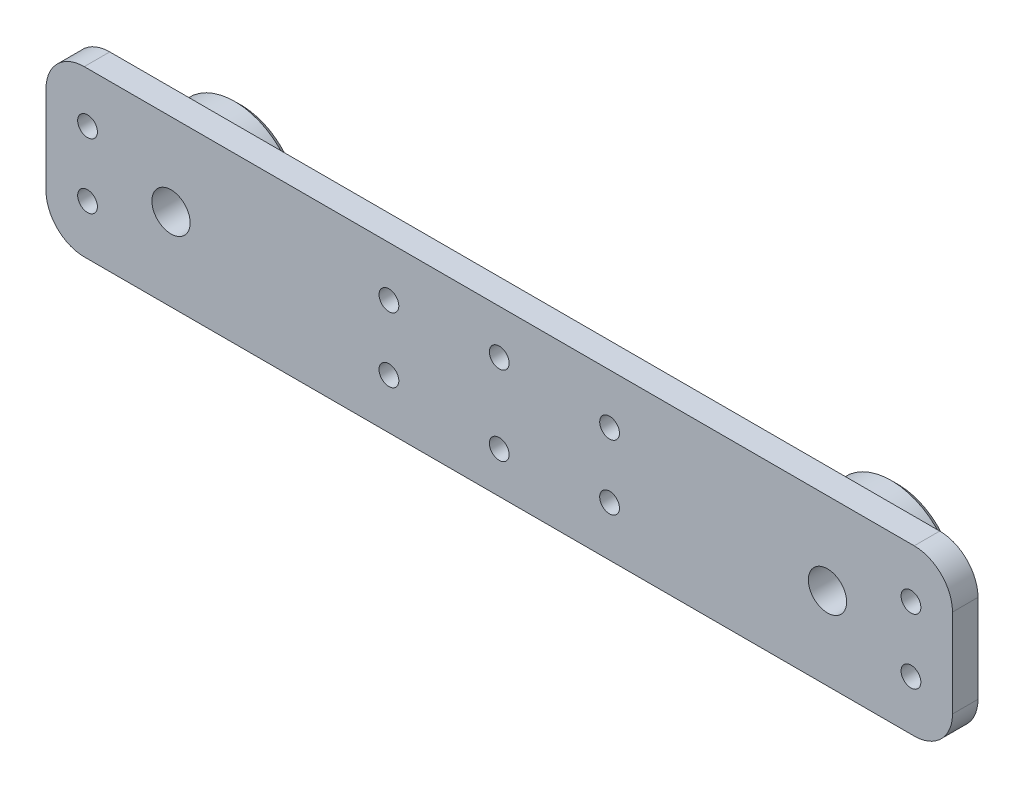
SolidWorks part; units mm, degrees
material "PET"
ref_plane "Front Plane" through (0, 0, 0) normal (0, 0, 1) x (1, 0, 0)
ref_plane "Top Plane" through (0, 0, 0) normal (0, 1, 0) x (1, 0, 0)
ref_plane "Right Plane" through (0, 0, 0) normal (1, 0, 0) x (0, 0, -1)
ref_plane "Plane1" through (0, 0, -8.279) normal (0, 0, -1) x (-1, 0, 0)
sketch "Sketch1" plane through (0, 0, -8.279) normal (0, 0, -1) x (-1, 0, 0)
  line L0 (-112, 9.158) -> (30.1427, 9.158)
  line L1 (30.1427, 9.158) -> (30.1427, 35)
  line L2 (30.1427, 35) -> (-112, 35)
  line L3 (-112, 35) -> (-112, 9.158)
extrude "Boss-Extrude1" add sketch "Sketch1" against normal blind 4
ref_plane "Plane2" through (0, 22.079, 0) normal (0, 1, 0) x (1, 0, 0)
sketch "Sketch2" plane through (0, 22.079, 0) normal (0, 1, 0) x (1, 0, 0)
  line L0 (-0.54, 15.279) -> (-10.54, 15.279)
  line L1 (-10.54, 15.279) -> (-10.54, 8.279)
  line L2 (-10.54, 8.279) -> (-0.54, 8.279)
  line L3 (-0.54, 8.279) -> (-0.54, 15.279)
  line L4 (-10.54, 15.279) -> (-10.54, 8.279) construction
revolve "Revolve1" add sketch "Sketch2" angle 360 about L4
sketch "Sketch3" plane through (0, 22.079, 0) normal (0, 1, 0) x (1, 0, 0)
  line L0 (102.397, 15.279) -> (92.397, 15.279)
  line L1 (92.397, 15.279) -> (92.397, 8.279)
  line L2 (92.397, 8.279) -> (102.397, 8.279)
  line L3 (102.397, 8.279) -> (102.397, 15.279)
  line L4 (92.397, 15.279) -> (92.397, 8.279) construction
revolve "Revolve2" add sketch "Sketch3" angle 360 about L4
hole_wizard "Ø3.1 (3.1) Diameter Hole1" positions "Sketch5" profile "Sketch4" hole size "Ø3.1" standard "ANSI Metric"
sketch "Sketch5" plane through (0, 0, -4.279) normal (0, 0, 1) x (1, 0, 0)
  point P0 (40.9286, 28.0395)
  point P1 (40.9286, 15.6185)
  point P2 (58.2273, 27.164)
  point P3 (23.63, 27.164)
  point P4 (-23.63, 27.164)
  point P5 (-23.63, 16.994)
  point P6 (23.63, 16.994)
  point P7 (58.2273, 16.994)
  point P8 (105.4873, 27.164)
  point P9 (105.4873, 16.994)
sketch "Sketch4" plane through (40.9286, 28.0395, -4.279) normal (1, 0, 0) x (0, -1, 0)
  line L0 (0, 0) -> (0, 11)
  line L1 (0, 11) -> (1.55, 11)
  line L2 (1.55, 11) -> (1.55, 0)
  line L5 (1.55, 0) -> (0, 0)
  line L11 (0, -6.35) -> (0, 107.95) construction
  dimension "Thru Hole Dia." = 3.1
  dimension "Thru Hole Depth" = 11
hole_wizard "Ø6.0 (6) Diameter Hole1" positions "Sketch7" profile "Sketch6" hole size "Ø6.0" standard "ANSI Metric"
sketch "Sketch7" plane through (0, 0, -15.279) normal (0, 0, -1) x (-1, 0, 0)
  point P0 (-92.397, 22.0793)
  point P1 (10.54, 22.079)
sketch "Sketch6" plane through (92.397, 22.0793, -15.279) normal (1, 0, 0) x (0, 1, 0)
  line L0 (0, 0) -> (0, 11)
  line L1 (0, 11) -> (3, 11)
  line L2 (3, 11) -> (3, 0)
  line L5 (3, 0) -> (0, 0)
  line L11 (0, -6.35) -> (0, 107.95) construction
  dimension "Thru Hole Dia." = 6
  dimension "Thru Hole Depth" = 11
chamfer "Chamfer1" distance 1 angle 45 4 edges at (92.397, 32.079, -8.279) (-10.54, 32.079, -8.279) (102.397, 22.079, -15.279) (-0.54, 22.079, -15.279)
fillet "Fillet1" radius 6 4 edges at (-30.1427, 35, -6.279) (112, 35, -6.279) (-30.1427, 9.158, -6.279) (112, 9.158, -6.279)
